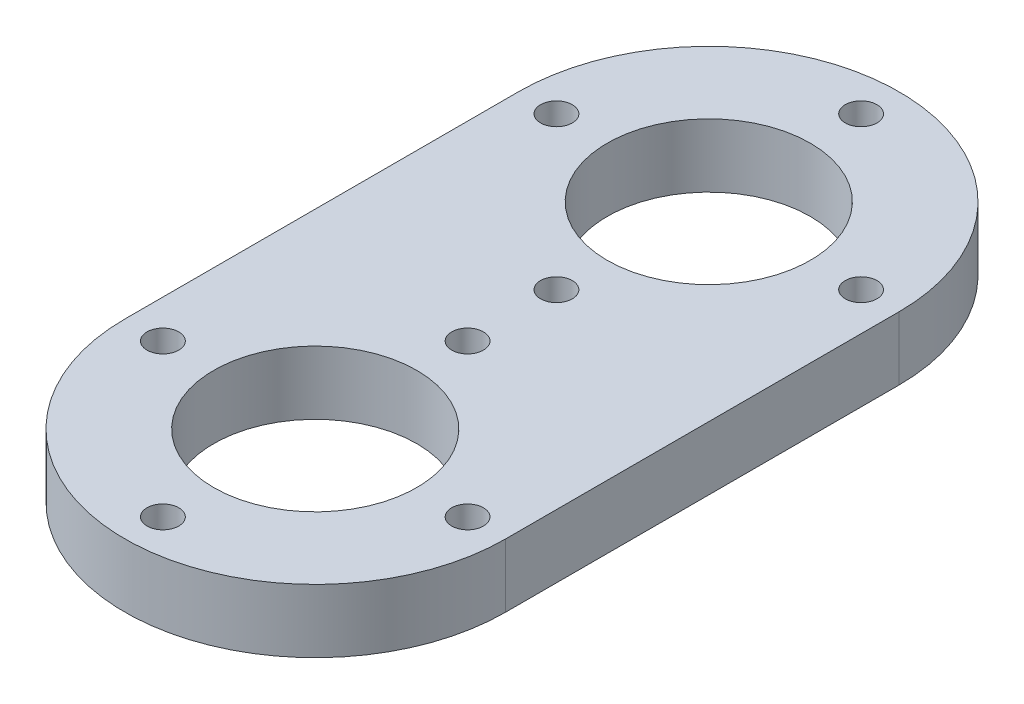
SolidWorks part; units mm, degrees
ref_plane "Alzado" through (0, 0, 0) normal (0, 0, 1) x (1, 0, 0)
ref_plane "Planta" through (0, 0, 0) normal (0, 1, 0) x (1, 0, 0)
ref_plane "Vista lateral" through (0, 0, 0) normal (1, 0, 0) x (0, 0, -1)
sketch "Croquis1" plane through (0, 0, 0) normal (0, 1, 0) x (1, 0, 0)
  line L0 (0, 31) -> (0, -31) construction
  line L5 (30, 31) -> (30, -31)
  line L6 (-30, 31) -> (-30, -31)
  arc A0 (30, 31) -> (-30, 31) centre (0, 31) ccw
  arc A1 (-30, -31) -> (30, -31) centre (0, -31) ccw
  circle A2 centre (0, -31) radius 16
  circle A3 centre (0, 31) radius 16
  point P3 (0, 0)
  dimension "D2" = 30
  dimension "D3" = 32
  dimension "D1" = 62
extrude "Saliente-Extruir1" add sketch "Croquis1" along normal blind 10
sketch "Sketch1" plane through (0, 10, 0) normal (0, 1, 0) x (1, 0, 0)
  line L0 (0, 31) -> (24, 31) construction
  circle A0 centre (24, 31) radius 2.5
  dimension "D1" = 24
  dimension "D2" = 5
extrude "Cut-Extrude1" cut sketch "Sketch1" against normal through all
pattern_circular "CirPattern1" count 4 over 360 about axis through (0, 0, -31) along (0, 1, 0) of "Cut-Extrude1"
mirror "Mirror1" about plane through (0, 0, 0) normal (0, 0, 1) of "CirPattern1", "Cut-Extrude1"
